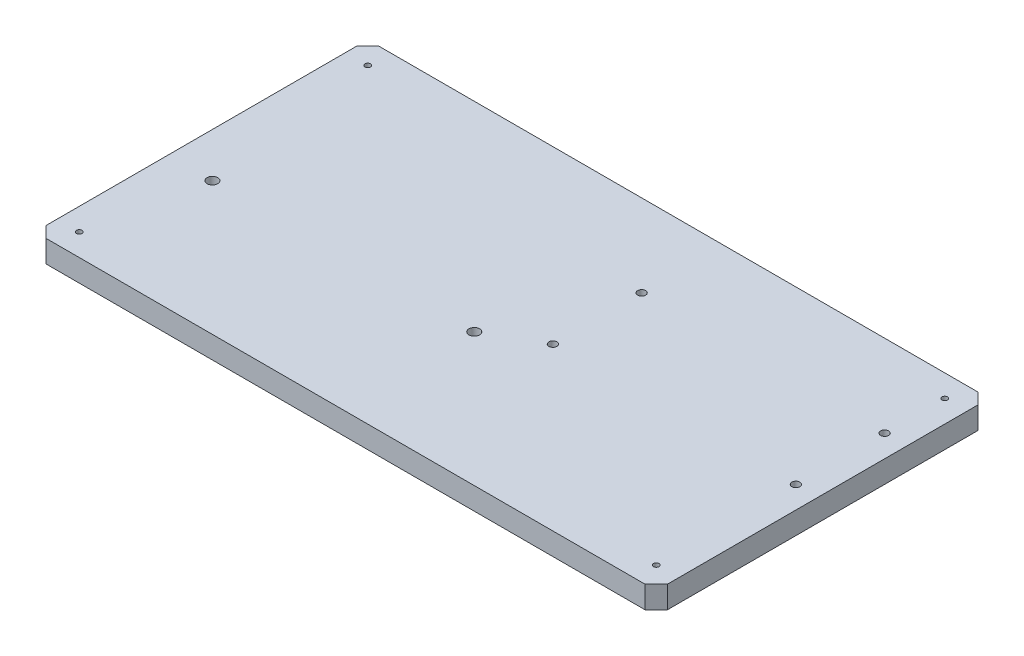
SolidWorks part; units mm, degrees
material "A5083"
ref_plane "Front Plane" through (0, 0, 0) normal (0, 0, 1) x (1, 0, 0)
ref_plane "Top Plane" through (0, 0, 0) normal (0, 1, 0) x (1, 0, 0)
ref_plane "Right Plane" through (0, 0, 0) normal (1, 0, 0) x (0, 0, -1)
sketch "Sketch1" plane through (0, 0, 0) normal (0, 1, 0) x (1, 0, 0)
  line L0 (0, 145) -> (5, 150)
  line L1 (5, 0) -> (275, 0)
  line L2 (0, 5) -> (0, 145)
  line L3 (5, 150) -> (275, 150)
  line L4 (280, 5) -> (280, 145)
  line L5 (275, 150) -> (280, 145)
  line L6 (275, 0) -> (280, 5)
  line L7 (0, 5) -> (5, 0)
  point P0 (0, 0)
  point P1 (280, 150)
  point P2 (0, 150)
  point P3 (280, 0)
  dimension "D1" = 280
  dimension "D2" = 150
extrude "Boss-Extrude1" add sketch "Sketch1" against normal blind 10
hole_wizard "CBORE for M4 Pan Head Screw1" positions "Sketch2" profile "Sketch3" counterbore size "M4" standard "JIS" end condition through all
sketch "Sketch2" plane through (0, -10, 0) normal (0, -1, 0) x (-1, 0, 0)
  line L1 (-5, 0) -> (-275, 0) construction
  line L2 (0, 145) -> (0, 5) construction
  point P9 (-138, 60)
  point P11 (-20, 60)
  dimension "D1" = 20
  dimension "D2" = 118
  dimension "D3" = 60
sketch "Sketch3" plane through (138, -10, -60) normal (1, 0, 0) x (0, 0, -1)
  line L0 (0, 0) -> (0, 10)
  line L1 (0, 10) -> (2.4, 10)
  line L3 (2.4, 10) -> (2.4, 5)
  line L4 (2.4, 5) -> (4.5, 5)
  line L5 (4.5, 5) -> (4.5, 0)
  line L7 (4.5, 0) -> (0, 0)
  line L11 (0, -6.35) -> (0, 107.95) construction
  dimension "Thru Hole Dia." = 4.8
  dimension "Thru Hole Depth" = 10
  dimension "C'Bore Dia." = 9
  dimension "C'Bore Depth" = 5
hole_wizard "M3x0.5 Tapped Hole1" positions "Sketch6" profile "Sketch7" tap size "M3x0.5" standard "JIS" end condition through all
sketch "Sketch6" plane through (0, -10, 0) normal (0, -1, 0) x (-1, 0, 0)
  line L0 (-5, 0) -> (-275, 0) construction
  line L1 (0, 145) -> (0, 5) construction
  line L2 (-275, 150) -> (-5, 150) construction
  line L3 (-280, 5) -> (-280, 145) construction
  point P0 (-10, 10)
  point P2 (-10, 140)
  point P4 (-270, 140)
  point P6 (-270, 10)
  dimension "D1" = 10
  dimension "D2" = 10
  dimension "D3" = 10
  dimension "D4" = 10
sketch "Sketch7" plane through (10, -10, -10) normal (1, 0, 0) x (0, 0, -1)
  line L0 (0, 0) -> (0, 10)
  line L1 (0, 10) -> (1.25, 10)
  line L2 (1.25, 10) -> (1.25, 0)
  line L5 (1.25, 0) -> (0, 0)
  line L11 (0, -6.35) -> (0, 107.95) construction
  dimension "Thru Tap Drill Dia." = 2.5
  dimension "Thru Tap Drill Depth" = 10
cosmetic thread "Hole Thread1" parameters "D2"=3
cosmetic thread "Hole Thread2" parameters "D2"=3
cosmetic thread "Hole Thread3" parameters "D2"=3
cosmetic thread "Hole Thread4" parameters "D2"=3
hole_wizard "CBORE for M3 Pan Head Screw1" positions "Sketch8" profile "Sketch9" counterbore size "M3" standard "JIS" end condition through all
sketch "Sketch8" plane through (0, -10, 0) normal (0, -1, 0) x (-1, 0, 0)
  line L0 (-280, 5) -> (-280, 145) construction
  point P6 (-160.5, 112.9227)
  point P9 (-160.5, 72.9227)
  point P19 (-270, 112.9227)
  point P21 (-270, 72.9227)
  point P26 (0, 0)
  point P27 (0, 0)
  point P28 (0, 0)
  dimension "D1" = 10
sketch "Sketch9" plane through (160.5, -10, -112.9227) normal (1, 0, 0) x (0, 0, -1)
  line L0 (0, 0) -> (0, 10)
  line L1 (0, 10) -> (1.8, 10)
  line L3 (1.8, 10) -> (1.8, 5)
  line L4 (1.8, 5) -> (3.5, 5)
  line L5 (3.5, 5) -> (3.5, 0)
  line L7 (3.5, 0) -> (0, 0)
  line L11 (0, -6.35) -> (0, 107.95) construction
  dimension "Thru Hole Dia." = 3.6
  dimension "Thru Hole Depth" = 10
  dimension "C'Bore Dia." = 7
  dimension "C'Bore Depth" = 5
